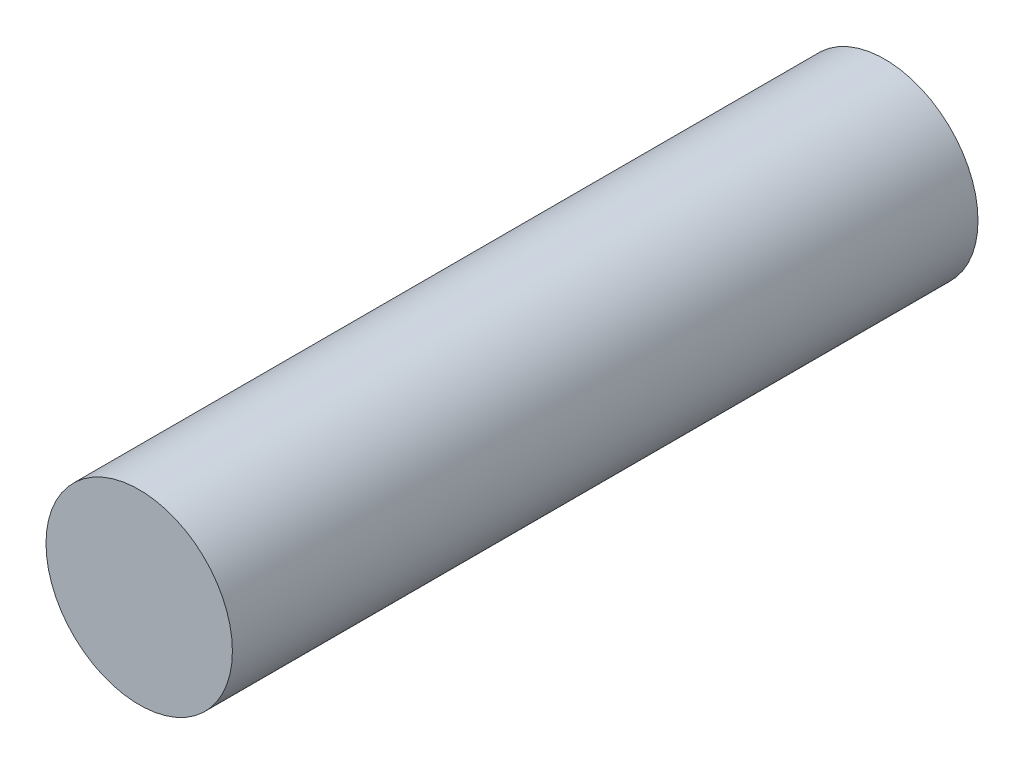
SolidWorks part; units mm, degrees
ref_plane "前视基准面" through (0, 0, 0) normal (0, 0, 1) x (1, 0, 0)
ref_plane "上视基准面" through (0, 0, 0) normal (0, 1, 0) x (1, 0, 0)
ref_plane "右视基准面" through (0, 0, 0) normal (1, 0, 0) x (0, 0, -1)
other "Configuration Table"
sketch "Profile1" plane through (0, 0, 0) normal (0, 0, 1) x (1, 0, 0)
  circle A0 centre (0, 0) radius 5
sketch "Path1" plane through (0, 0, 0) normal (1, 0, 0) x (0, 0, -1)
  line L0 (0, 0) -> (-40, 0)
sweep "sweep_circle10_path40" add profiles "Profile1" path "Path1"
